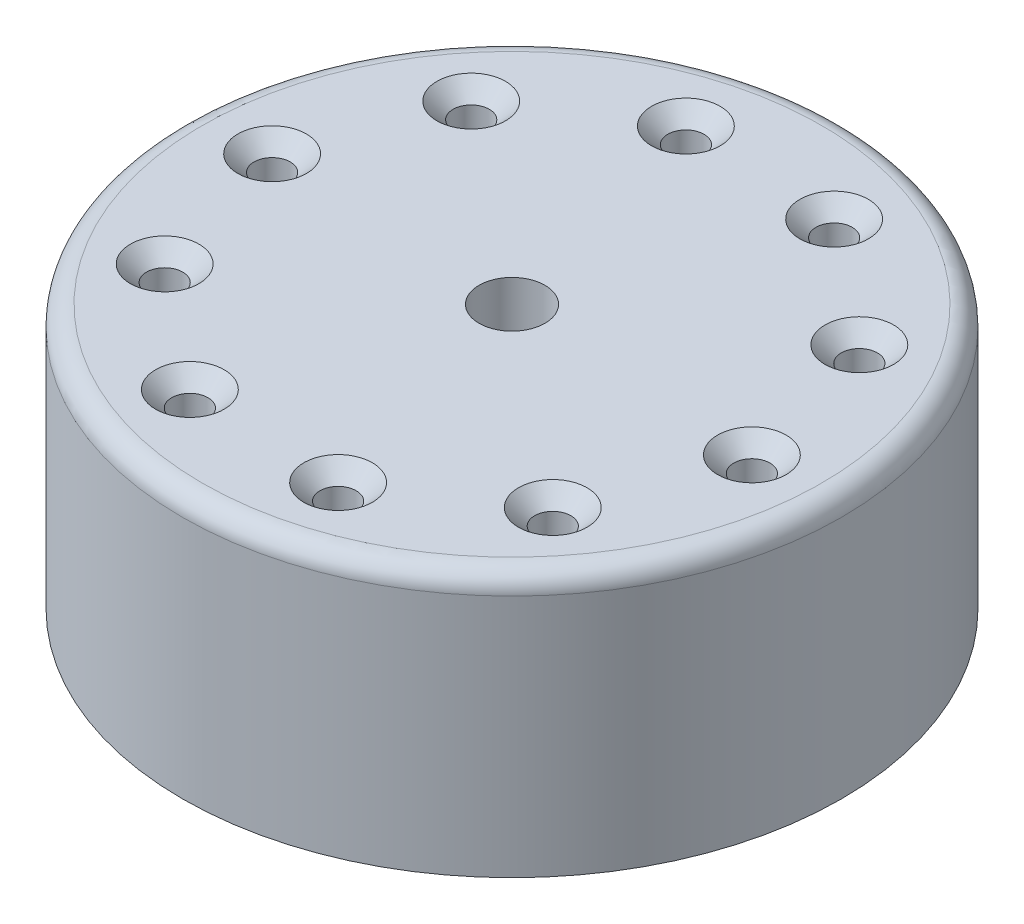
SolidWorks part; units mm, degrees
ref_plane "Front Plane" through (0, 0, 0) normal (0, 0, 1) x (1, 0, 0)
ref_plane "Top Plane" through (0, 0, 0) normal (0, 1, 0) x (1, 0, 0)
ref_plane "Right Plane" through (0, 0, 0) normal (1, 0, 0) x (0, 0, -1)
sketch "Sketch1" plane through (0, 0, 0) normal (0, 1, 0) x (1, 0, 0)
  circle A0 centre (0, 0) radius 50
  dimension "D1" = 100
extrude "Boss-Extrude1" add sketch "Sketch1" along normal blind 40
hole_wizard "CSK for M5 Countersunk Flat Head Screw1" positions "Sketch3" profile "Sketch5" countersink size "M5" standard "ISO"
sketch "Sketch3" plane through (0, 40, 0) normal (0, 1, 0) x (1, 0, 0)
  point P0 (-37.9839, 1.5858)
sketch "Sketch5" plane through (-37.9839, 40, -1.5858) normal (1, 0, 0) x (0, 0, 1)
  line L0 (0, 0) -> (0, 16.6524)
  line L1 (0, 16.6524) -> (2.75, 15)
  line L2 (2.75, 15) -> (2.75, 2.45)
  line L3 (2.75, 2.45) -> (5.2, 0)
  line L5 (5.2, 0) -> (0, 0)
  line L6 (-2.75, 2.45) -> (-5.2, 0) construction
  line L10 (0, 16.6524) -> (-2.75, 15) construction
  line L11 (0, -6.35) -> (0, 107.95) construction
  dimension "Hole Dia." = 5.5
  dimension "Hole Depth" = 15
  dimension "Near C'Sink Dia." = 10.4
  dimension "Near C'Sink Angle" = 90
  dimension "Drill Angle" = 118
pattern_circular "CirPattern1" count 10 over 360 about axis through (0, 0, 0) along (0, 1, 0) of "CSK for M5 Countersunk Flat Head Screw1"
sketch "Sketch6" plane through (0, 0, 0) normal (0, -1, 0) x (-1, 0, 0)
  circle A0 centre (0, 0) radius 30
  circle A1 centre (0, 0) radius 5
  dimension "D1" = 60
  dimension "D2" = 10
sketch "Sketch7" plane through (0, 0, 0) normal (1, 0, 0) x (0, 0, -1)
  line L0 (0, -15.6297) -> (0, 25.5763) construction
fillet "Fillet2" radius 3 1 edges at (0, 40, 50)
sketch "Sketch8" plane through (0, 0, 0) normal (1, 0, 0) x (0, 0, -1)
  line L0 (-50, 0) -> (0, 0)
  line L1 (0, 0) -> (0, -15.6297)
  arc A0 (0, -15.6297) -> (-50, 0) centre (5.7634, 90.5986) cw
revolve "Revolve2" add sketch "Sketch8" angle 360 about L1
sketch "Sketch9" plane through (0, 40, 0) normal (0, 1, 0) x (1, 0, 0)
  circle A0 centre (0, 0) radius 5
extrude "Cut-Extrude2" cut sketch "Sketch9" against normal through all
ref_plane "Plane1" through (0, 25, 0) normal (0, 1, 0) x (1, 0, 0)
sketch "Sketch10" plane through (0, 25, 0) normal (0, 1, 0) x (1, 0, 0)
  circle A0 centre (0, 0) radius 47
  circle A1 centre (0, 0) radius 30
extrude "Cut-Extrude3" cut sketch "Sketch10" against normal blind 15
sketch "Sketch14" plane through (0, 10, 0) normal (0, 1, 0) x (1, 0, 0)
  line L0 (-30.7564, -22.3458) -> (0, 0) construction
  line L1 (0, 0) -> (-38.017, 0) construction
  line L2 (0, 0) -> (-30.7564, 22.3458) construction
  line L3 (-11.7479, 36.1563) -> (0, 0) construction
  line L4 (0, 0) -> (11.7479, 36.1563) construction
  line L5 (30.7564, 22.3458) -> (0, 0) construction
  line L6 (0, 0) -> (38.017, 0) construction
  line L7 (30.7564, -22.3458) -> (0, 0) construction
  line L8 (0, 0) -> (11.7479, -36.1563) construction
  line L9 (-11.7479, -36.1563) -> (0, 0) construction
  circle A0 centre (0, 0) radius 38.017 construction
  circle A1 centre (38.017, 0) radius 2.75
  circle A2 centre (30.7564, -22.3458) radius 2.75
  circle A3 centre (11.7479, -36.1563) radius 2.75
  circle A4 centre (-11.7479, -36.1563) radius 2.75
  circle A5 centre (-30.7564, -22.3458) radius 2.75
  circle A6 centre (-38.017, 0) radius 2.75
  circle A7 centre (-30.7564, 22.3458) radius 2.75
  circle A8 centre (-11.7479, 36.1563) radius 2.75
  circle A9 centre (11.7479, 36.1563) radius 2.75
  circle A10 centre (30.7564, 22.3458) radius 2.75
  circle A11 centre (0, 0) radius 30
  circle A12 centre (0, 0) radius 5
  point P26 (0, 0)
  dimension "D1" = 5.5
  dimension "D2" = 10
sketch "Sketch15" plane through (0, 10, 0) normal (0, 1, 0) x (1, 0, 0)
  line L0 (4.5271, -2.1226) -> (25.0672, -16.505)
  line L1 (3.4708, -3.5991) -> (23.4884, -18.6834)
  line L2 (30.7564, -22.3458) -> (0, 0) construction
  arc A0 (23.4884, -18.6834) -> (25.0672, -16.505) centre (0, 0) ccw
  arc A1 (3.4708, -3.5991) -> (4.5271, -2.1226) centre (0, 0) ccw
  dimension "D1" = 1
  dimension "D2" = 1
extrude "Cut-Extrude4" cut sketch "Sketch15" along normal blind 5
pattern_circular "CirPattern2" count 10 over 360 about axis through (0, 0, 0) along (0, 1, 0) of "Cut-Extrude4"
